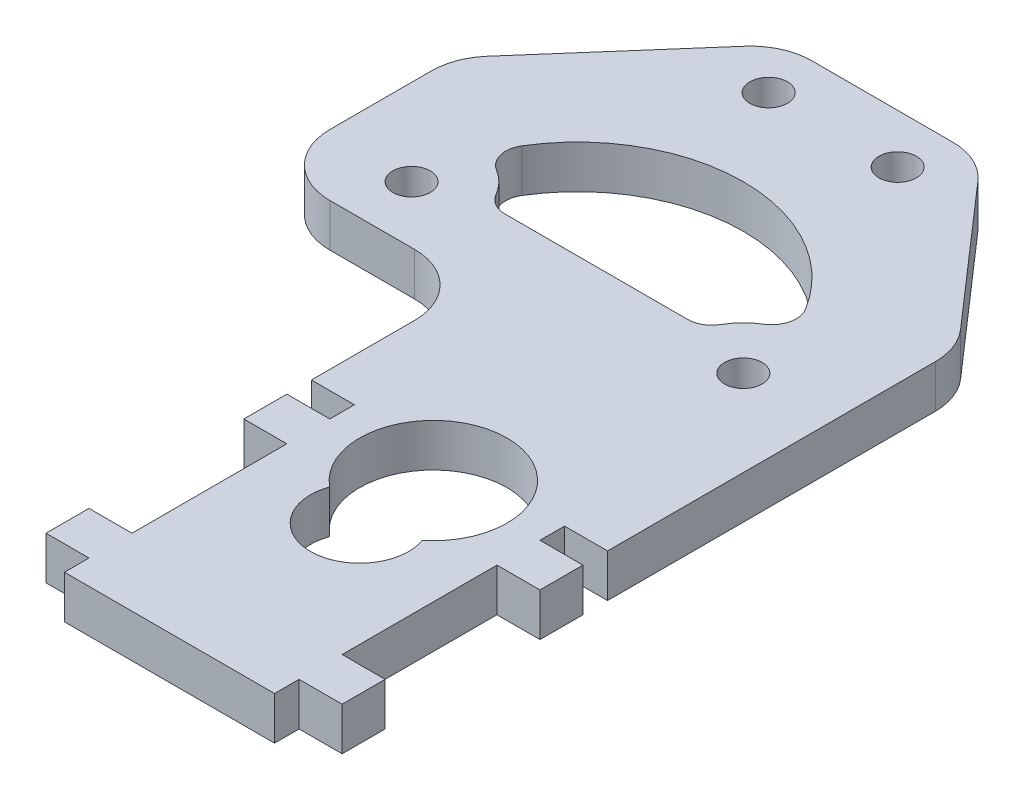
SolidWorks part; units mm, degrees
material "Balsa"
ref_plane "Front Plane" through (0, 0, 0) normal (0, 0, 1) x (1, 0, 0)
ref_plane "Top Plane" through (0, 0, 0) normal (0, 1, 0) x (1, 0, 0)
ref_plane "Right Plane" through (0, 0, 0) normal (1, 0, 0) x (0, 0, -1)
sketch "Sketch2" plane through (0, 0, 0) normal (0, 1, 0) x (1, 0, 0)
  line L0 (0, 29.4591) -> (0, -6.6242) construction
  line L1 (-33.1139, 0) -> (21.8397, 0) construction
  line L2 (-8, 29.4591) -> (8, 29.4591)
  line L3 (8, 29.4591) -> (20.5, 15.15)
  line L4 (20.5, 15.15) -> (20.5, -15.15) construction
  line L6 (-20.5, -37) -> (20.5, -37) construction
  line L7 (-8, 29.4591) -> (-20.5, 15.15)
  line L8 (-20.5, 15.15) -> (-20.5, -15.15) construction
  line L10 (-13.5, 4.65) -> (13.5, 4.65) construction
  line L11 (13.5, 4.65) -> (8.45, -15.5276) construction
  line L12 (8.712, 6.175) -> (-8.712, 6.175)
  line L13 (20.5, -15.15) -> (20.5, -37) construction
  line L14 (-20.5, -15.15) -> (-20.5, -37) construction
  line L15 (-3.6, -37) -> (-3.6, 0) construction
  line L16 (-3.6, 0) -> (-20.5, 0)
  line L17 (-20.5, 15.15) -> (-20.5, 0)
  line L18 (20.5, -37) -> (-3.6, -37) construction
  line L19 (17, -37) -> (17, -35)
  line L20 (17, -13.4) -> (20.5, -13.4)
  line L21 (20.5, -35) -> (17, -35)
  line L22 (20.5, -31.5) -> (17, -31.5)
  line L23 (20.5, -15.4) -> (17, -15.4)
  line L24 (20.5, -18.9) -> (17, -18.9)
  line L25 (17, -15.4) -> (17, -13.4)
  line L26 (17, -31.5) -> (17, -18.9)
  line L27 (20.5, -15.4) -> (20.5, -18.9)
  line L28 (20.5, -31.5) -> (20.5, -35)
  line L29 (20.5, 15.15) -> (20.5, -13.4)
  line L30 (8.45, -4.9318) -> (8.45, -37) construction
  line L31 (-0.1, -37) -> (-0.1, -35)
  line L32 (-0.1, -13.4) -> (-3.6, -13.4)
  line L33 (-0.1, -15.4) -> (-3.6, -15.4)
  line L34 (-0.1, -18.9) -> (-3.6, -18.9)
  line L35 (-0.1, -31.5) -> (-3.6, -31.5)
  line L36 (-0.1, -35) -> (-3.6, -35)
  line L37 (-0.1, -15.4) -> (-0.1, -13.4)
  line L38 (-0.1, -31.5) -> (-0.1, -18.9)
  line L39 (-3.6, -35) -> (-3.6, -31.5)
  line L40 (-3.6, -15.4) -> (-3.6, -18.9)
  line L41 (-3.6, 0) -> (-3.6, -13.4)
  line L42 (17, -37) -> (-0.1, -37)
  circle A0 centre (-5.25, 25.4591) radius 1.525
  circle A1 centre (-13.5, 4.65) radius 1.525
  circle A2 centre (13.5, 4.65) radius 1.525
  circle A3 centre (5.25, 25.4591) radius 1.525
  circle A4 centre (8.45, -15.5276) radius 6 construction
  circle A5 centre (-13.5, 4.65) radius 5.025 construction
  circle A6 centre (13.5, 4.65) radius 5.025 construction
  arc A7 (12.5648, 9.5872) -> (-12.5648, 9.5872) centre (0, 4.65) ccw
  arc A8 (-8.712, 6.175) -> (-12.5648, 9.5872) centre (-13.5, 4.65) ccw
  arc A9 (8.712, 6.175) -> (12.5648, 9.5872) centre (13.5, 4.65) cw
  arc A10 (4.6788, -20.1943) -> (12.2212, -20.1943) centre (8.45, -21.5276) ccw
  arc A11 (4.6788, -20.1943) -> (12.2212, -20.1943) centre (8.45, -15.5276) cw
  point P10 (20.5, 0)
  point P16 (0, -29.4591)
  point P28 (0, 4.65)
  point P30 (0, 6.175)
  dimension "D5" = 3.05
  dimension "D11" = 12
  dimension "D12" = 3.5
  dimension "D14" = 13.5
  dimension "D24" = 4
  dimension "D1" = 16
  dimension "D2" = 30.3
  dimension "D3" = 19
  dimension "D4" = 20.5
  dimension "D6" = 4
  dimension "D7" = 2.75
  dimension "D8" = 27
  dimension "D9" = 10.5
  dimension "D13" = 3.05
  dimension "D15" = 37
  dimension "D16" = 24.1
  dimension "D17" = 23.6
  dimension "D18" = 3.5
  dimension "D19" = 2
  dimension "D20" = 3.5
  dimension "D21" = 2
  dimension "D22" = 3.5
  dimension "D23" = 3.5
  dimension "D25" = 20.8
extrude "Boss-Extrude1" add sketch "Sketch2" along normal blind 3.5
fillet "Fillet1" radius 5 6 edges at (-3.6, 1.75, 0) (-20.5, 1.75, 0) (-20.5, 1.75, -15.15) (-8, 1.75, -29.4591) (8, 1.75, -29.4591) (20.5, 1.75, -15.15)
fillet "Fillet2" radius 2 4 edges at (8.712, 1.75, -6.175) (12.5648, 1.75, -9.5872) (-8.712, 1.75, -6.175) (-12.5648, 1.75, -9.5872)
